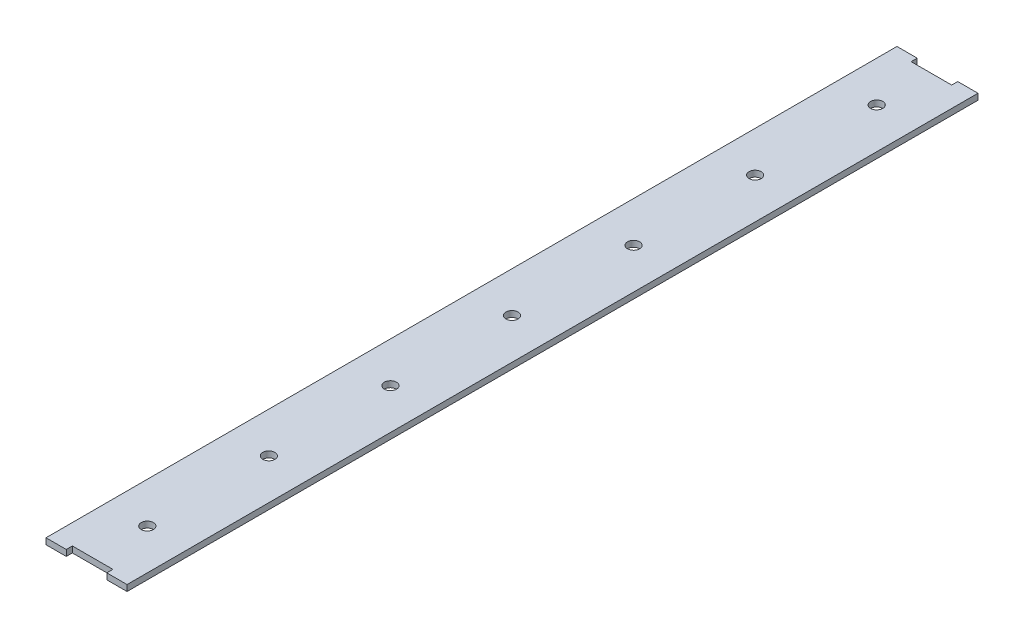
SolidWorks part; units mm, degrees
ref_plane "Front Plane" through (0, 0, 0) normal (0, 0, 1) x (1, 0, 0)
ref_plane "Top Plane" through (0, 0, 0) normal (0, 1, 0) x (1, 0, 0)
ref_plane "Right Plane" through (0, 0, 0) normal (1, 0, 0) x (0, 0, -1)
sketch "Sketch1" plane through (0, 0, 0) normal (0, 1, 0) x (1, 0, 0)
  line L1 (-20, 0) -> (20, 0)
  line L2 (-20, 0) -> (-20, 420)
  line L3 (-20, 420) -> (20, 420)
  line L4 (20, 0) -> (20, 420)
  line L5 (-10, 0) -> (10, 0)
  line L6 (-10, 0) -> (-10, 3)
  line L7 (-10, 3) -> (10, 3)
  line L8 (10, 0) -> (10, 3)
  line L9 (-10, 420) -> (10, 420)
  line L10 (-10, 420) -> (-10, 417)
  line L11 (-10, 417) -> (10, 417)
  line L12 (10, 420) -> (10, 417)
  circle A0 centre (0, 30) radius 3
  circle A2 centre (0, 90) radius 3
  circle A3 centre (0, 150) radius 3
  circle A4 centre (0, 210) radius 3
  circle A5 centre (0, 270) radius 3
  circle A6 centre (0, 330) radius 3
  circle A7 centre (0, 390) radius 3
  point P4 (0, 0)
  point P8 (0, 3)
  point P29 (0, 420)
  point P30 (0, 417)
  dimension "D3" = 6
  dimension "D1" = 420
  dimension "D2" = 40
  dimension "D4" = 30
  dimension "D6" = 60
  dimension "D7" = 3
  dimension "D8" = 20
  dimension "D9" = 3
  dimension "D10" = 20
  dimension "D5" = 7
extrude "Boss-Extrude1" add sketch "Sketch1" along normal blind 3 contours L3 L12 L11 L10 L2 L1 L6 L7 L8 L4 A7 A6 A5 A4 A3 A2 A0
